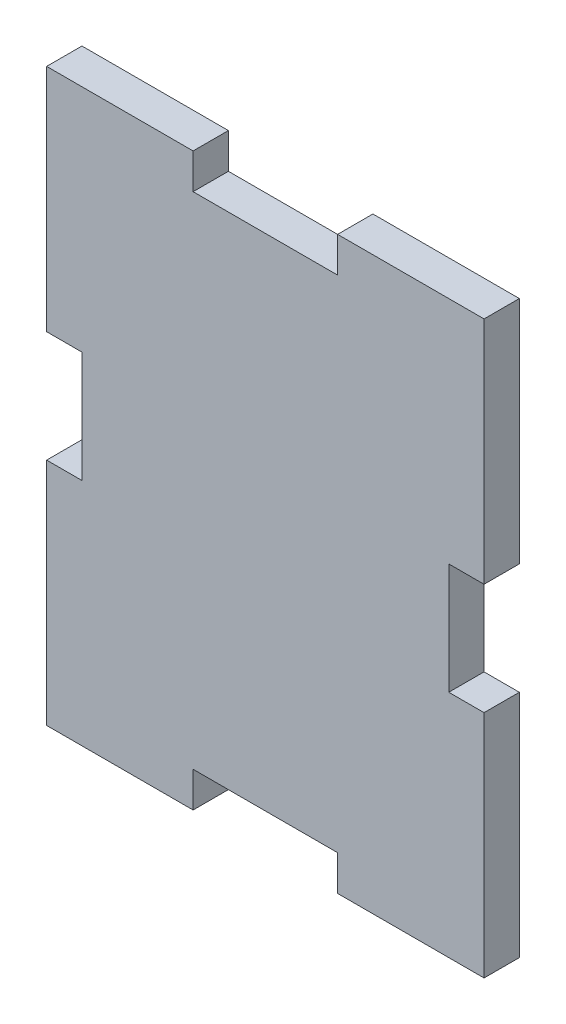
SolidWorks part; units mm, degrees
ref_plane "Front Plane" through (0, 0, 0) normal (0, 0, 1) x (1, 0, 0)
ref_plane "Top Plane" through (0, 0, 0) normal (0, 1, 0) x (1, 0, 0)
ref_plane "Right Plane" through (0, 0, 0) normal (1, 0, 0) x (0, 0, -1)
sketch "Sketch1" plane through (0, 0, 0) normal (0, 0, 1) x (1, 0, 0)
  line L0 (0, 0) -> (0, 41.35)
  line L5 (0, 41.35) -> (6.35, 41.35)
  line L6 (6.35, 41.35) -> (6.35, 61.35)
  line L7 (6.35, 61.35) -> (0, 61.35)
  line L8 (0, 61.35) -> (0, 102.7)
  line L10 (78.7, 102.7) -> (78.7, 61.35)
  line L11 (78.7, 61.35) -> (72.35, 61.35)
  line L12 (72.35, 61.35) -> (72.35, 41.35)
  line L13 (72.35, 41.35) -> (78.7, 41.35)
  line L14 (78.7, 41.35) -> (78.7, 0)
  line L16 (0, 102.7) -> (26.35, 102.7)
  line L17 (26.35, 102.7) -> (26.35, 96.35)
  line L18 (26.35, 96.35) -> (52.35, 96.35)
  line L19 (52.35, 96.35) -> (52.35, 102.7)
  line L20 (52.35, 102.7) -> (78.7, 102.7)
  line L21 (0, 0) -> (26.35, 0)
  line L22 (26.35, 0) -> (26.35, 6.35)
  line L23 (26.35, 6.35) -> (52.35, 6.35)
  line L24 (52.35, 6.35) -> (52.35, 0)
  line L25 (52.35, 0) -> (78.7, 0)
  point P21 (39.35, 6.35)
  dimension "D2" = 102.7
  dimension "D3" = 90
  dimension "D4" = 66
  dimension "D5" = 78.7
  dimension "D6" = 26
  dimension "D7" = 26
  dimension "D8" = 20
  dimension "D9" = 20
  dimension "D10" = 41.35
  dimension "D11" = 41.35
  dimension "D12" = 78.7
  dimension "D13" = 26.35
  dimension "D14" = 26.35
  dimension "D15" = 6.35
  dimension "D16" = 6.35
  dimension "D17" = 6.35
extrude "Boss-Extrude1" add sketch "Sketch1" along normal blind 6.35
